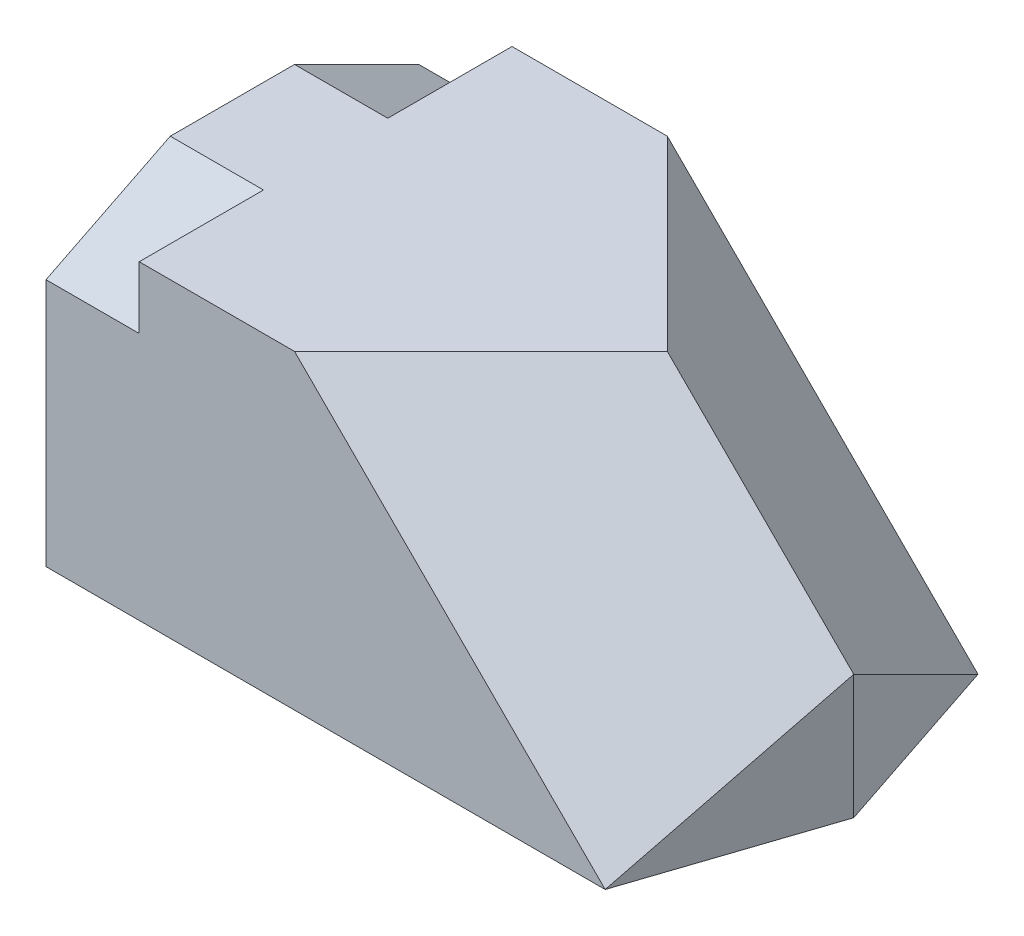
SolidWorks part; units mm, degrees
material "Alloy Steel"
ref_plane "Front Plane" through (0, 0, 0) normal (0, 0, 1) x (1, 0, 0)
ref_plane "Top Plane" through (0, 0, 0) normal (0, 1, 0) x (1, 0, 0)
ref_plane "Right Plane" through (0, 0, 0) normal (1, 0, 0) x (0, 0, -1)
sketch "Croquis2" plane through (0, 0, 0) normal (0, 0, 1) x (1, 0, 0)
  line L0 (0, 0) -> (100, 0)
  line L1 (100, 0) -> (100, 50)
  line L2 (100, 50) -> (0, 50)
  line L3 (0, 50) -> (0, 0)
  point P3 (-1.2813, 56.0316)
  dimension "D1" = 100
  dimension "D2" = 100
  dimension "D3" = 50
extrude "Saliente-Extruir1" add sketch "Croquis2" along normal mid plane 60
sketch "Croquis3" plane through (0, 0, 0) normal (-1, 0, 0) x (0, 0, 1)
  line L0 (30, 50) -> (30, 40)
  line L1 (30, 50) -> (30, 0) construction
  line L2 (30, 40) -> (10, 50)
  line L3 (30, 50) -> (-30, 50) construction
  line L4 (10, 50) -> (30, 50)
  dimension "D1" = 20
  dimension "D2" = 10
extrude "Cortar-Extruir1" cut sketch "Croquis3" against normal blind 15
sketch "Croquis4" plane through (0, 0, 0) normal (0, -1, 0) x (1, 0, 0)
  line L0 (100, 0) -> (90, 30)
  line L1 (100, 30) -> (100, -30) construction
  line L2 (0, 30) -> (100, 30) construction
  line L3 (90, 30) -> (100, 30)
  line L4 (100, 30) -> (100, 0)
  dimension "D1" = 10
extrude "Cortar-Extruir2" cut sketch "Croquis4" against normal blind 20
sketch "Croquis5" plane through (0, 0, 0) normal (0, 0, 1) x (1, 0, 0)
  line L0 (100, 20) -> (70, 50) construction
  line L1 (100, 50) -> (15, 50) construction
  dimension "D1" = 30
sketch "Croquis6" plane through (0, 50, 0) normal (0, 1, 0) x (1, 0, 0)
  line L0 (100, 0) -> (70, 0)
  line L1 (100, 0) -> (70, 0) construction
  line L2 (70, 0) -> (40, -30)
  line L3 (100, -30) -> (15, -30) construction
  line L4 (40, -30) -> (100, -30)
  line L5 (100, -30) -> (100, 0)
  dimension "D1" = 25
  dimension "D2" = 30
extrude "Cortar-Extruir3" cut sketch "Croquis6" along direction (-0.7071, 0.7071, 0) on the side against the normal through all
mirror "Simetría1" about plane through (0, 0, 0) normal (0, 0, 1) of "Cortar-Extruir1", "Cortar-Extruir2", "Cortar-Extruir3"
